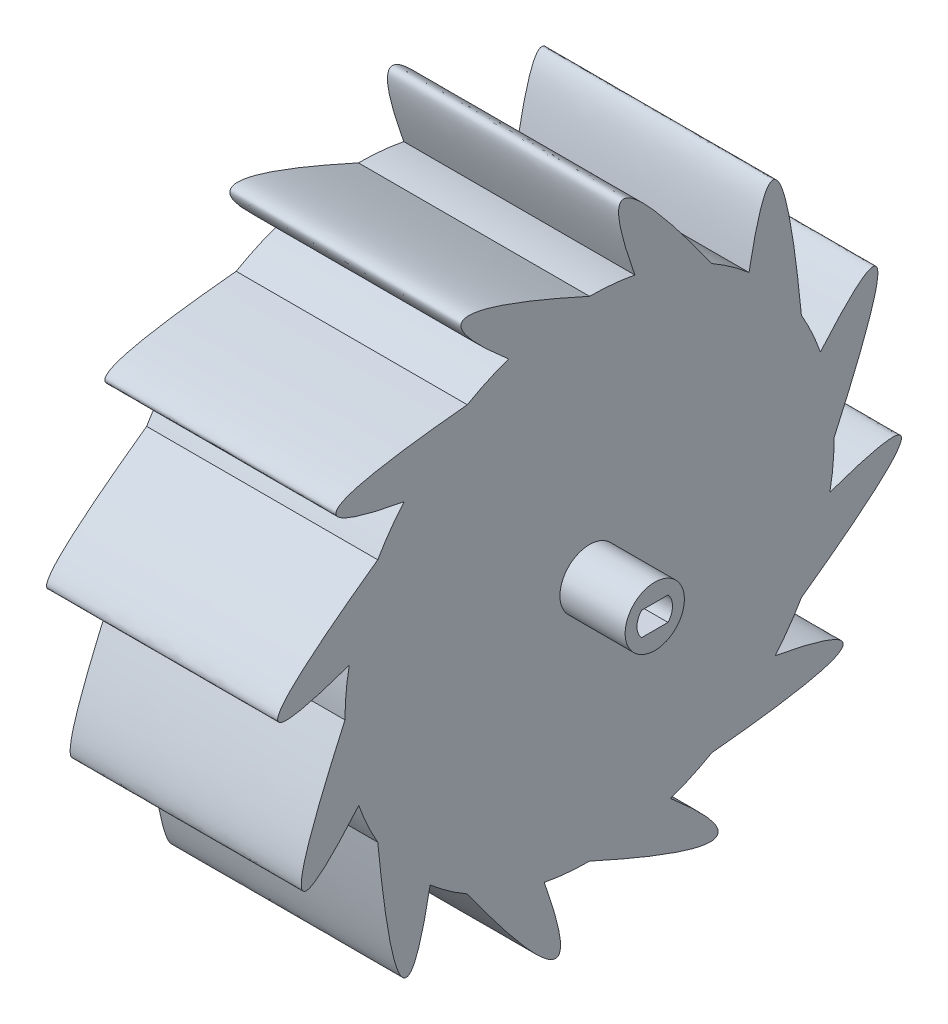
SolidWorks part; units mm, degrees
material "Nylon 101"
ref_plane "Front Plane" through (0, 0, 0) normal (0, 0, 1) x (1, 0, 0)
ref_plane "Top Plane" through (0, 0, 0) normal (0, 1, 0) x (1, 0, 0)
ref_plane "Right Plane" through (0, 0, 0) normal (1, 0, 0) x (0, 0, -1)
sketch "Sketch1" plane through (0, 0, 0) normal (1, 0, 0) x (0, 0, -1)
  circle A0 centre (0, 0) radius 5
  circle A1 centre (0, 0) radius 32.5
  dimension "D1" = 65
  dimension "D2" = 10
extrude "Boss-Extrude1" add sketch "Sketch1" against normal blind 35
sketch "Sketch2" plane through (-35, 0, 0) normal (-1, 0, 0) x (0, 0, 1)
  circle A0 centre (0, 0) radius 8.5
  circle A1 centre (0, 0) radius 1
  dimension "D1" = 2
  dimension "D2" = 17
extrude "Boss-Extrude2" add sketch "Sketch2" against normal blind 1 separate body
sketch "Sketch3" plane through (-35, 0, 0) normal (-1, 0, 0) x (0, 0, 1)
  line L0 (0, 0) -> (13.5, 0) construction
  line L1 (12.8938, 4) -> (20.6155, 4)
  line L2 (7.7886, -11.0267) -> (10.1748, -18.3705)
  line L3 (20.6155, -4) -> (12.8938, -4)
  line L4 (2.5663, -20.8426) -> (0.1802, -13.4988)
  line L5 (-8.0802, -10.8149) -> (-14.3272, -15.3536)
  line L6 (-19.0295, -8.8814) -> (-12.7824, -4.3427)
  line L7 (-12.7824, 4.3427) -> (-19.0295, 8.8814)
  line L8 (-14.3272, 15.3536) -> (-8.0802, 10.8149)
  line L9 (0.1802, 13.4988) -> (2.5663, 20.8426)
  line L10 (10.1748, 18.3705) -> (7.7886, 11.0267)
  line L11 (-2.2361, 2) -> (2.2361, 2)
  line L12 (-2.2361, -2) -> (2.2361, -2)
  circle A0 centre (0, 0) radius 32.5
  arc A1 (2.5663, -20.8426) -> (10.1748, -18.3705) centre (0, 0) ccw
  arc A2 (0.1802, -13.4988) -> (7.7886, -11.0267) centre (0, 0) ccw
  arc A3 (-12.7824, -4.3427) -> (-8.0802, -10.8149) centre (0, 0) ccw
  arc A4 (-19.0295, -8.8814) -> (-14.3272, -15.3536) centre (0, 0) ccw
  arc A5 (-14.3272, 15.3536) -> (-19.0295, 8.8814) centre (0, 0) ccw
  arc A6 (-8.0802, 10.8149) -> (-12.7824, 4.3427) centre (0, 0) ccw
  arc A7 (10.1748, 18.3705) -> (2.5663, 20.8426) centre (0, 0) ccw
  arc A8 (7.7886, 11.0267) -> (0.1802, 13.4988) centre (0, 0) ccw
  arc A9 (20.6155, -4) -> (20.6155, 4) centre (0, 0) ccw
  arc A10 (12.8938, -4) -> (12.8938, 4) centre (0, 0) ccw
  arc A11 (-2.2361, 2) -> (-2.2361, -2) centre (0, 0) ccw
  arc A12 (2.2361, -2) -> (2.2361, 2) centre (0, 0) ccw
  point P29 (0, 0)
  dimension "D1" = 27
  dimension "D2" = 42
  dimension "D4" = 6
  dimension "D3" = 4
  dimension "D6" = 2
  dimension "D5" = 5
extrude "Boss-Extrude4" add sketch "Sketch3" along normal blind 2
sketch "Sketch4" plane through (-37, 0, 0) normal (-1, 0, 0) x (0, 0, 1)
  circle A0 centre (0, 0) radius 32.5 construction
  circle A1 centre (0, 0) radius 32.5
  circle A2 centre (0, 0) radius 5 construction
  circle A3 centre (0, 0) radius 5
extrude "Boss-Extrude5" add sketch "Sketch4" along normal blind 2
sketch "Sketch5" plane through (-37, 0, 0) normal (-1, 0, 0) x (0, 0, 1)
  line L0 (2.2361, 2) -> (-2.2361, 2) construction
  line L1 (2.2361, 2) -> (-2.2361, 2)
  line L2 (-2.2361, -2) -> (2.2361, -2) construction
  line L3 (-2.2361, -2) -> (2.2361, -2)
  arc A0 (-2.2361, 2) -> (-2.2361, -2) centre (0, 0) ccw construction
  arc A1 (-2.2361, 2) -> (-2.2361, -2) centre (0, 0) ccw
  arc A2 (2.2361, -2) -> (2.2361, 2) centre (0, 0) ccw construction
  arc A3 (2.2361, -2) -> (2.2361, 2) centre (0, 0) ccw
  circle A4 centre (0, 0) radius 5
  dimension "D1" = 10
extrude "Boss-Extrude6" add sketch "Sketch5" against normal blind 48 separate body
sketch "Sketch6" plane through (-39, 0, 0) normal (-1, 0, 0) x (0, 0, 1)
  circle A0 centre (0, 0) radius 32.5
  arc A62 (-20.6359, 35.7424) -> (-26.8989, 31.3018) centre (0, 0) ccw
  arc A63 (-35.7424, 20.6359) -> (-38.9461, 13.6587) centre (0, 0) ccw
  arc A64 (-41.2717, 0) -> (-40.5576, -7.6442) centre (0, 0) ccw
  arc A65 (0, 41.2717) -> (-7.6442, 40.5576) centre (0, 0) ccw
  arc A66 (20.6359, 35.7424) -> (13.6587, 38.9461) centre (0, 0) ccw
  arc A67 (35.7424, 20.6359) -> (31.3018, 26.8989) centre (0, 0) ccw
  arc A68 (41.2717, 0) -> (40.5576, 7.6442) centre (0, 0) ccw
  arc A69 (-35.7424, -20.6359) -> (-31.3018, -26.8989) centre (0, 0) ccw
  arc A70 (35.7424, -20.6359) -> (38.9461, -13.6587) centre (0, 0) ccw
  arc A71 (20.6359, -35.7424) -> (26.8989, -31.3018) centre (0, 0) ccw
  arc A72 (0, -41.2717) -> (7.6442, -40.5576) centre (0, 0) ccw
  arc A73 (-20.6359, -35.7424) -> (-13.6587, -38.9461) centre (0, 0) ccw
  circle A74 centre (0, 0) radius 5 construction
  spline S0 degree 2 poles (0, 41.2717) (34.9011, 57.0949) (13.6587, 38.9461) knots 0 0 0 1 1 1
  spline S1 degree 2 poles (20.6359, 35.7424) (58.7727, 31.9951) (31.3018, 26.8989) knots 0 0 0 1 1 1
  spline S2 degree 2 poles (35.7424, 20.6359) (66.8961, -1.6778) (40.5576, 7.6442) knots 0 0 0 1 1 1
  spline S3 degree 2 poles (41.2717, 0) (57.0949, -34.9011) (38.9461, -13.6587) knots 0 0 0 1 1 1
  spline S4 degree 2 poles (35.7424, -20.6359) (31.9951, -58.7727) (26.8989, -31.3018) knots 0 0 0 1 1 1
  spline S5 degree 2 poles (20.6359, -35.7424) (-1.6778, -66.8961) (7.6442, -40.5576) knots 0 0 0 1 1 1
  spline S6 degree 2 poles (0, -41.2717) (-34.9011, -57.0949) (-13.6587, -38.9461) knots 0 0 0 1 1 1
  spline S7 degree 2 poles (-20.6359, -35.7424) (-58.7727, -31.9951) (-31.3018, -26.8989) knots 0 0 0 1 1 1
  spline S8 degree 2 poles (-35.7424, -20.6359) (-66.8961, 1.6778) (-40.5576, -7.6442) knots 0 0 0 1 1 1
  spline S9 degree 2 poles (-41.2717, 0) (-57.0949, 34.9011) (-38.9461, 13.6587) knots 0 0 0 1 1 1
  spline S10 degree 2 poles (-35.7424, 20.6359) (-31.9951, 58.7727) (-26.8989, 31.3018) knots 0 0 0 1 1 1
  spline S11 degree 2 poles (-20.6359, 35.7424) (1.6778, 66.8961) (-7.6442, 40.5576) knots 0 0 0 1 1 1
  point P42 (0, 0)
  point P71 (0, 0)
  point P82 (0, 0)
  point P83 (0, 0)
  point P99 (0, 0)
  dimension "D1" = 65
  dimension "D2" = 8.7717
  dimension "D3" = 8.7717
extrude "Boss-Extrude7" add sketch "Sketch6" against normal blind 39
